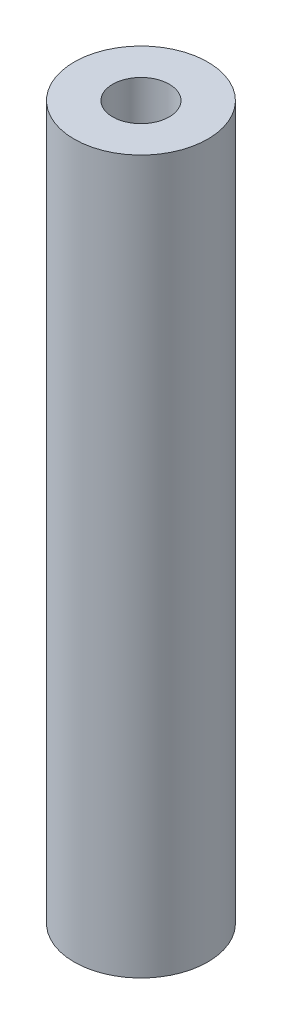
SolidWorks part; units mm, degrees
material "6061-T6 (SS)"
ref_plane "Front Plane" through (0, 0, 0) normal (0, 0, 1) x (1, 0, 0)
ref_plane "Top Plane" through (0, 0, 0) normal (0, 1, 0) x (1, 0, 0)
ref_plane "Right Plane" through (0, 0, 0) normal (1, 0, 0) x (0, 0, -1)
sketch "Sketch1" plane through (0, 0, 0) normal (0, 1, 0) x (1, 0, 0)
  circle A0 centre (0, 0) radius 4.7625
  dimension "D1" = 9.525
extrude "Boss-Extrude1" add sketch "Sketch1" along normal mid plane 50.8
hole_wizard "#10-32 Tapped Hole1" positions "3DSketch1" profile "Sketch2" tap size "#10-32" standard "ANSI Inch"
sketch3d "3DSketch1"
  line L0 (0, 25.4, 0) -> (0, -25.4, 0) construction
  point P2 (0, -25.4, 0)
  point P11 (0, 25.4, 0)
sketch "Sketch2" plane through (0, -25.4, 0) normal (1, 0, 0) x (0, 0, -1)
  line L0 (0, 0) -> (0, 13.1513)
  line L1 (0, 13.1513) -> (2.0193, 11.938)
  line L2 (2.0193, 11.938) -> (2.0193, 0)
  line L5 (2.0193, 0) -> (0, 0)
  line L10 (0, 13.1513) -> (-2.0193, 11.938) construction
  line L11 (0, -6.35) -> (0, 107.95) construction
  dimension "Tap Drill Dia." = 4.0386
  dimension "Tap Drill Depth" = 11.938
  dimension "Drill Angle" = 118
cosmetic thread "Hole Thread1"
cosmetic thread "Hole Thread2"
